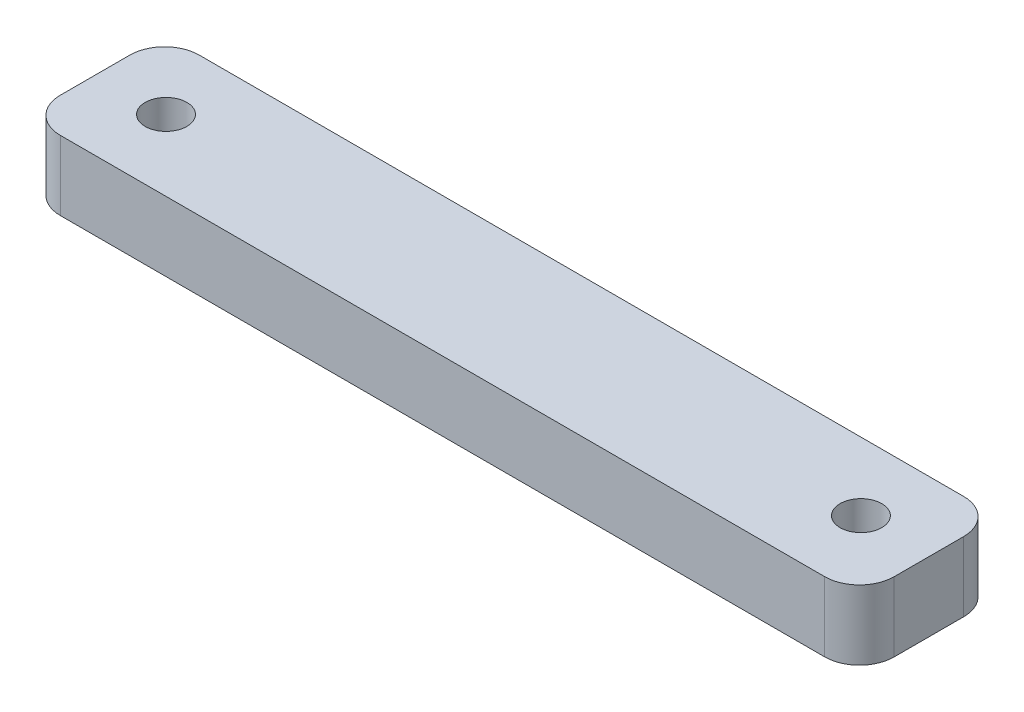
SolidWorks part; units mm, degrees
ref_plane "Front Plane" through (0, 0, 0) normal (0, 0, 1) x (1, 0, 0)
ref_plane "Top Plane" through (0, 0, 0) normal (0, 1, 0) x (1, 0, 0)
ref_plane "Right Plane" through (0, 0, 0) normal (1, 0, 0) x (0, 0, -1)
sketch "Sketch1" plane through (0, 0, 0) normal (0, 1, 0) x (1, 0, 0)
  line L1 (6.35, 0) -> (146.05, 0)
  line L2 (0, 6.35) -> (0, 19.05)
  line L3 (6.35, 25.4) -> (146.05, 25.4)
  line L4 (152.4, 6.35) -> (152.4, 19.05)
  arc A0 (152.4, 6.35) -> (146.05, 0) centre (146.05, 6.35) cw
  arc A1 (152.4, 19.05) -> (146.05, 25.4) centre (146.05, 19.05) ccw
  arc A2 (6.35, 0) -> (0, 6.35) centre (6.35, 6.35) cw
  arc A3 (0, 19.05) -> (6.35, 25.4) centre (6.35, 19.05) cw
  circle A4 centre (12.7, 12.9688) radius 3.81
  circle A5 centre (139.7, 12.9688) radius 3.81
  point P7 (152.4, 0)
  point P10 (152.4, 25.4)
  point P13 (0, 0)
  point P16 (0, 25.4)
  dimension "D3" = 12.7
  dimension "D4" = 12.7
  dimension "D1" = 152.4
  dimension "D2" = 25.4
extrude "Boss-Extrude1" add sketch "Sketch1" along normal blind 12.7
